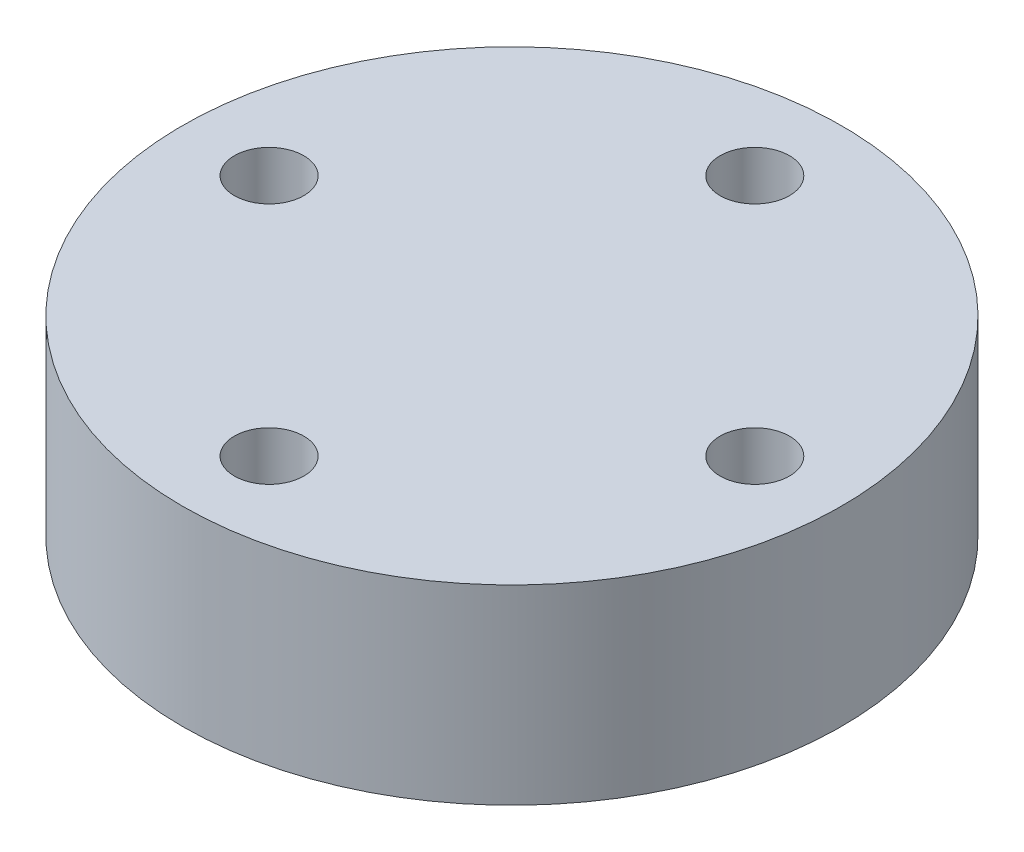
SolidWorks part; units mm, degrees
ref_plane "Спереди" through (0, 0, 0) normal (0, 0, 1) x (1, 0, 0)
ref_plane "Сверху" through (0, 0, 0) normal (0, 1, 0) x (1, 0, 0)
ref_plane "Справа" through (0, 0, 0) normal (1, 0, 0) x (0, 0, -1)
sketch "Эскиз1" plane through (0, 0, 0) normal (0, 1, 0) x (1, 0, 0)
  circle A0 centre (0, 0) radius 9.5
  circle A1 centre (0, 0) radius 7 construction
  circle A2 centre (0, 0) radius 8 construction
  circle A3 centre (0, 7) radius 1
  circle A4 centre (7, 0) radius 1
  circle A5 centre (0, -7) radius 1
  circle A6 centre (-7, 0) radius 1
  dimension "D1" = 14
  dimension "D2" = 16
  dimension "D3" = 19
extrude "Бобышка-Вытянуть1" add sketch "Эскиз1" along normal blind 5.5
